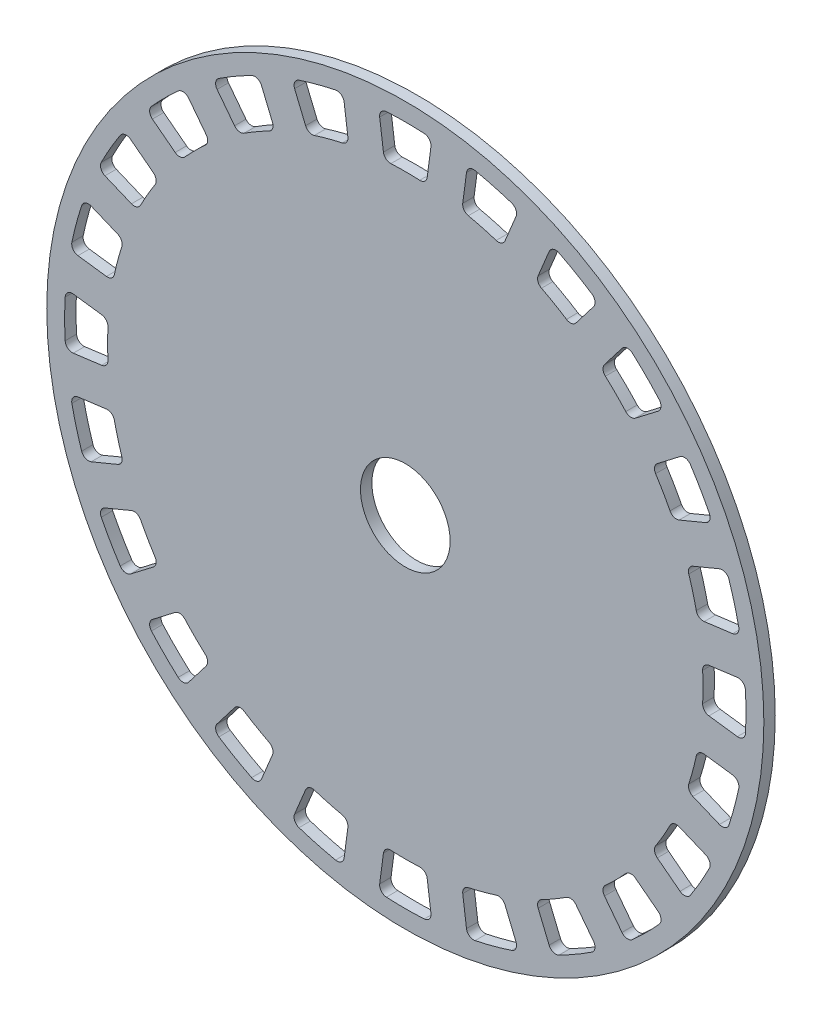
SolidWorks part; units mm, degrees
material "6061-T6 (SS)"
ref_plane "Front Plane" through (0, 0, 0) normal (0, 0, 1) x (1, 0, 0)
ref_plane "Top Plane" through (0, 0, 0) normal (0, 1, 0) x (1, 0, 0)
ref_plane "Right Plane" through (0, 0, 0) normal (1, 0, 0) x (0, 0, -1)
sketch "Sketch1" plane through (0, 0, 0) normal (0, 0, 1) x (1, 0, 0)
  circle A0 centre (0, 0) radius 100 construction
  circle A1 centre (0, 0) radius 100
  circle A2 centre (0, 0) radius 12.5 construction
  circle A3 centre (0, 0) radius 12.5
extrude "Plate Extrude" add sketch "Sketch1" along normal up to vertex (3.175 mm away)
sketch "Sketch2" plane through (0, 0, 3.175) normal (0, 0, 1) x (1, 0, 0)
  line L0 (0, 0) -> (13.0526, 99.1445) construction
  line L1 (0, 0) -> (-13.0526, 99.1445) construction
  line L2 (0, 0) -> (0, 100) construction
  line L4 (-6.5826, 50) -> (6.5826, 50) construction
  line L5 (5.8601, 82.8185) -> (7.4264, 94.7159)
  line L6 (-5.8601, 82.8185) -> (-7.4264, 94.7159)
  line L7 (6.6433, 88.7672) -> (11.6005, 88.1146) construction
  line L8 (-6.6433, 88.7672) -> (-11.6005, 88.1146) construction
  line L9 (7.4264, 94.7159) -> (8.0791, 99.6731) construction
  circle A0 centre (0, 0) radius 100 construction
  arc A1 (-13.0526, 99.1445) -> (13.0526, 99.1445) centre (0, 0) cw construction
  arc A2 (-7.4264, 94.7159) -> (7.4264, 94.7159) centre (0, 0) cw
  arc A3 (-5.8601, 82.8185) -> (5.8601, 82.8185) centre (0, 0) cw
  point P9 (0, 50)
  dimension "D1" = 15
  dimension "D2" = 5
  dimension "D3" = 12
extrude "Coil Mounting Cut" cut sketch "Sketch2" against normal through all
fillet "Coil Mounting Fillet" radius 2 4 edges at (5.8601, 82.8185, 1.5875) (-5.8601, 82.8185, 1.5875) (7.4264, 94.7159, 1.5875) (-7.4264, 94.7159, 1.5875)
pattern_circular "CirPattern1" count 24 over 360 about axis through (0, 0, 0) along (0, 0, 1) of "Coil Mounting Cut", "Coil Mounting Fillet"
equation "\"D1@Sketch2\"=360/24"
